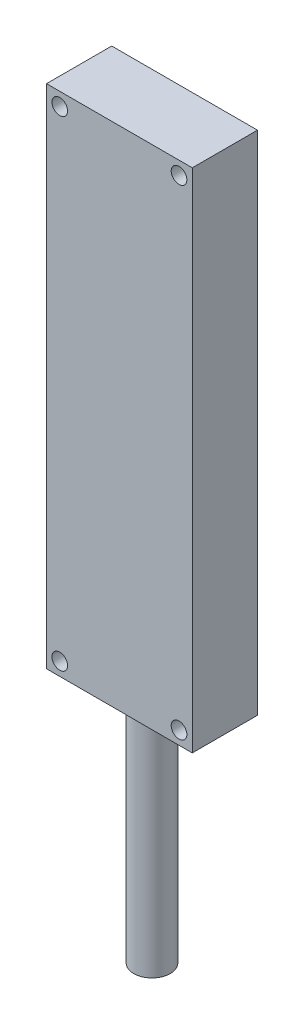
SolidWorks part; units mm, degrees
ref_plane "Front Plane" through (0, 0, 0) normal (0, 0, 1) x (1, 0, 0)
ref_plane "Top Plane" through (0, 0, 0) normal (0, 1, 0) x (1, 0, 0)
ref_plane "Right Plane" through (0, 0, 0) normal (1, 0, 0) x (0, 0, -1)
sketch "Sketch1" plane through (0, 0, 0) normal (0, 0, 1) x (1, 0, 0)
  line L1 (13.97, -48.57) -> (-13.97, -48.57)
  line L2 (13.97, -48.57) -> (13.97, 48.57)
  line L3 (13.97, 48.57) -> (-13.97, 48.57)
  line L4 (-13.97, -48.57) -> (-13.97, 48.57)
  line L5 (13.97, -48.57) -> (-13.97, 48.57) construction
  line L6 (13.97, 48.57) -> (-13.97, -48.57) construction
  point P0 (0, 0)
  dimension "D1" = 97.14
  dimension "D2" = 27.94
extrude "Boss-Extrude1" add sketch "Sketch1" along normal blind 12.5
sketch "Sketch2" plane through (0, 0, 0) normal (0, 0, -1) x (-1, 0, 0)
  line L0 (-13.97, 0) -> (13.97, 0) construction
  line L3 (-13.97, -48.57) -> (-13.97, 48.57) construction
  line L4 (13.97, 48.57) -> (13.97, -48.57) construction
  line L5 (0, 48.57) -> (0, -48.57) construction
  line L6 (-13.97, 48.57) -> (13.97, 48.57) construction
  line L7 (13.97, -48.57) -> (-13.97, -48.57) construction
  circle A0 centre (-11.43, 46.04) radius 1.5
  circle A1 centre (-11.43, -46.04) radius 1.5
  circle A2 centre (11.43, 46.04) radius 1.5
  circle A3 centre (11.43, -46.04) radius 1.5
  dimension "D1" = 3
  dimension "D6" = 22.86
  dimension "D4" = 46.04
  dimension "D5" = 11.43
  dimension "D7" = 92.08
  dimension "D2" = 2
  dimension "D3" = 2
extrude "Cut-Extrude1" cut sketch "Sketch2" against normal blind 23
sketch "Sketch3" plane through (0, -48.57, 0) normal (0, -1, 0) x (1, 0, 0)
  line L0 (-13.97, 0) -> (13.97, 0) construction
  circle A0 centre (0, 6.25) radius 3.5
  dimension "D1" = 7
  dimension "D2" = 6.25
extrude "Boss-Extrude2" add sketch "Sketch3" along normal blind 45 contours A0
